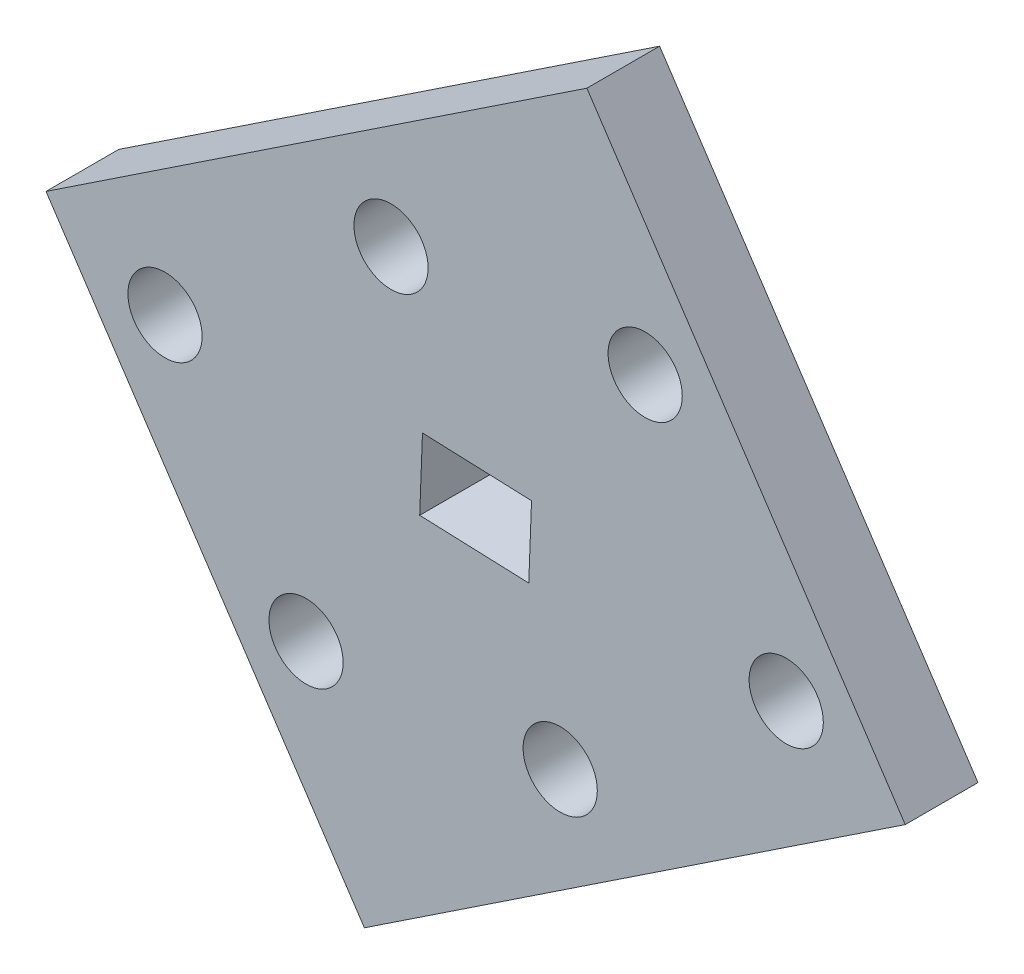
SolidWorks part; units mm, degrees
ref_plane "Front Plane" through (0, 0, 0) normal (0, 0, 1) x (1, 0, 0)
ref_plane "Top Plane" through (0, 0, 0) normal (0, 1, 0) x (1, 0, 0)
ref_plane "Right Plane" through (0, 0, 0) normal (1, 0, 0) x (0, 0, -1)
sketch "Sketch1" plane through (0, 0, 0) normal (0, 0, 1) x (1, 0, 0)
  line L0 (-3.662, -82.9082) -> (70.6732, -33.4555)
  line L1 (-3.662, -82.9082) -> (-47.4195, -17.1337)
  line L2 (70.6732, -33.4555) -> (26.9157, 32.319)
  line L3 (-47.4195, -17.1337) -> (26.9157, 32.319)
  line L4 (-3.662, -82.9082) -> (26.9157, 32.319) construction
  line L5 (70.6732, -33.4555) -> (-47.4195, -17.1337) construction
  line L6 (54.3159, -26.9219) -> (-31.0622, -23.6673) construction
  circle A2 centre (0, 0) radius 5.1
  circle A3 centre (0, 0) radius 5.1
  circle A5 centre (34.9296, 2.2187) radius 5.1
  circle A6 centre (34.9296, 2.2187) radius 5.1
  circle A9 centre (54.3159, -26.9219) radius 5.1
  circle A10 centre (54.3159, -26.9219) radius 5.1
  circle A14 centre (23.2537, -50.5892) radius 5.1
  circle A15 centre (23.2537, -50.5892) radius 5.1
  circle A19 centre (-11.6759, -52.8079) radius 5.1
  circle A20 centre (-11.6759, -52.8079) radius 5.1
  circle A22 centre (-31.0622, -23.6673) radius 5.1
  circle A23 centre (-31.0622, -23.6673) radius 5.1
  point P0 (11.6268, -25.2946)
  point P1 (11.6268, -25.2946)
  point P2 (-57.2196, -14.2662)
  dimension "D2" = 0.1
  dimension "D3" = 0.1
  dimension "D4" = 0.1
  dimension "D5" = 0.1
  dimension "D7" = 12
  dimension "D8" = 10
  dimension "D9" = 10
  dimension "D1" = 0.1
  dimension "D6" = 0.1
extrude "Boss-Extrude1" add sketch "Sketch1" against normal blind 10
sketch "Sketch2" plane through (0, 0, 0) normal (0, 0, 1) x (1, 0, 0)
  line L0 (4.3227, -20.0125) -> (19.3119, -20.5839)
  line L1 (4.3227, -20.0125) -> (3.9418, -30.0053)
  line L2 (19.3119, -20.5839) -> (18.9309, -30.5767)
  line L3 (3.9418, -30.0053) -> (18.9309, -30.5767)
  line L4 (4.3227, -20.0125) -> (18.9309, -30.5767) construction
  line L5 (19.3119, -20.5839) -> (3.9418, -30.0053) construction
  line L7 (54.3159, -26.9219) -> (-31.0622, -23.6673) construction
  point P0 (0, 0)
  point P1 (11.6268, -25.2946)
  dimension "D1" = 15
  dimension "D2" = 10
extrude "Cut-Extrude1" cut sketch "Sketch2" against normal up to next
